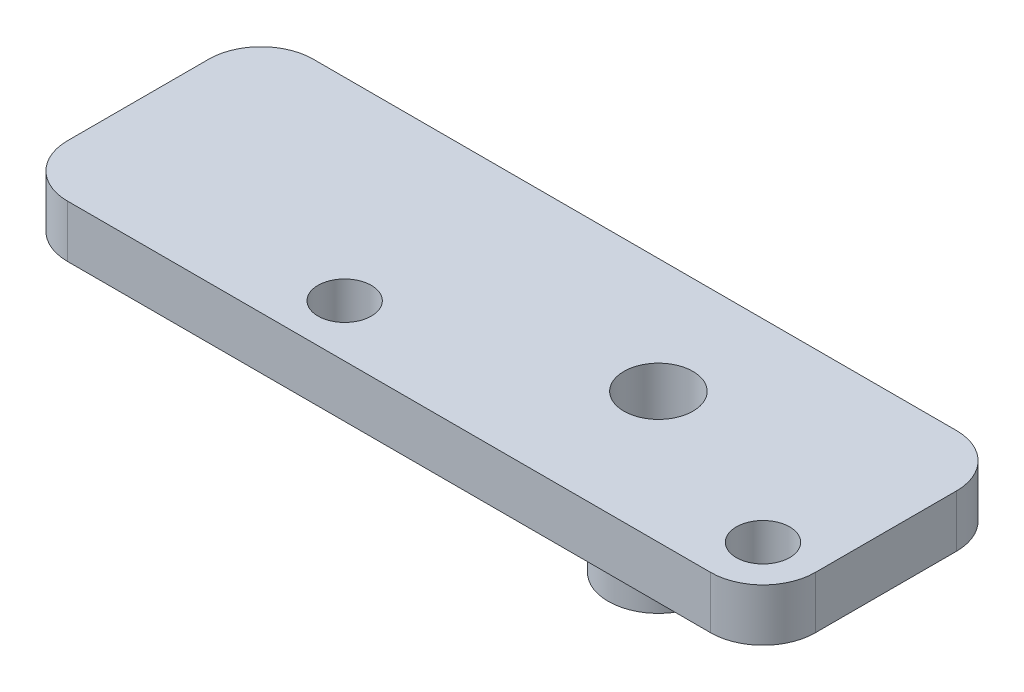
SolidWorks part; units mm, degrees
ref_plane "Front Plane" through (0, 0, 0) normal (0, 0, 1) x (1, 0, 0)
ref_plane "Top Plane" through (0, 0, 0) normal (0, 1, 0) x (1, 0, 0)
ref_plane "Right Plane" through (0, 0, 0) normal (1, 0, 0) x (0, 0, -1)
sketch "Sketch1" plane through (0, 0, 0) normal (0, 1, 0) x (1, 0, 0)
  line L0 (0, 0) -> (-75, 0) construction
  line L1 (0, 0) -> (0, -50000) construction
  line L2 (0, -15) -> (-45, -15) construction
  line L3 (0, -15) -> (35, -15) construction
  line L5 (45, -25) -> (-98, -25)
  line L6 (45, -25) -> (45, 22)
  line L7 (45, 22) -> (-98, 22)
  line L8 (-98, -25) -> (-98, 22)
  circle A0 centre (0, 0) radius 6.6
  circle A1 centre (-75, 0) radius 18 construction
  circle A2 centre (-45, -15) radius 5.1
  circle A3 centre (35, -15) radius 5.1
  dimension "D1" = 15
  dimension "D2" = 10
  dimension "D3" = 22
  dimension "D4" = 10
  dimension "D5" = 23
  dimension "D6" = 75
extrude "Boss-Extrude1" add sketch "Sketch1" along normal blind 10
fillet "Fillet1" radius 10 1 edges at (-98, 5, -22)
fillet "Fillet2" radius 10 1 edges at (-98, 5, 25)
fillet "Fillet3" radius 10 1 edges at (45, 5, 25)
fillet "Fillet4" radius 10 1 edges at (45, 5, -22)
sketch "Sketch2" plane through (0, 0, 0) normal (0, -1, 0) x (1, 0, 0)
  circle A0 centre (0, 0) radius 9.6
  circle A1 centre (0, 0) radius 6.6
  dimension "D1" = 3
extrude "Boss-Extrude2" add sketch "Sketch2" along normal blind 20
